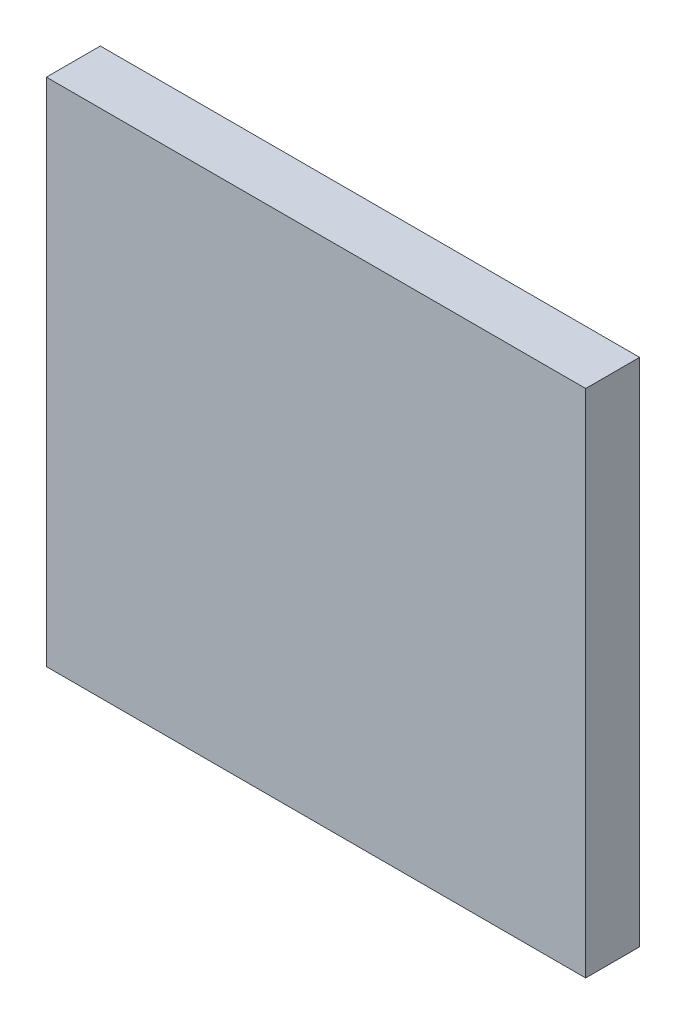
SolidWorks part; units mm, degrees
ref_plane "Front Plane" through (0, 0, 0) normal (0, 0, 1) x (1, 0, 0)
ref_plane "Top Plane" through (0, 0, 0) normal (0, 1, 0) x (1, 0, 0)
ref_plane "Right Plane" through (0, 0, 0) normal (1, 0, 0) x (0, 0, -1)
sketch "Sketch1" plane through (0, 0, 0) normal (0, 0, 1) x (1, 0, 0)
  circle A0 centre (0, 0) radius 19.939
  dimension "D1" = 39.878
extrude "circle extrude" add sketch "Sketch1" along normal blind 12.7
sketch "Sketch3" plane through (0, 0, 0) normal (1, 0, 0) x (0, 0, -1)
  line L0 (0, 19.8374) -> (0, -19.8374) construction
  line L1 (-12.7, 19.939) -> (0, 19.939)
  line L2 (-12.7, 19.939) -> (-12.7, -19.939)
  line L3 (-12.7, -19.939) -> (0, -19.939)
  line L4 (0, 19.939) -> (0, -19.939)
  line L5 (-12.7, -19.939) -> (0, -19.939) construction
extrude "rectangle extrude" add sketch "Sketch3" along normal blind 68.58
sketch "Sketch2" plane through (0, 0, 12.7) normal (0, 0, 1) x (1, 0, 0)
  circle A0 centre (0, 0) radius 18.034
  dimension "D1" = 36.068
extrude "cricle cut" cut sketch "Sketch2" against normal through all
sketch "Sketch4" plane through (0, 0, 12.7) normal (0, 0, 1) x (1, 0, 0)
  line L0 (68.58, 19.939) -> (68.58, -19.939) construction
  line L1 (0, 18.034) -> (66.675, 18.034)
  line L2 (0, 18.034) -> (0, -18.034)
  line L3 (0, -18.034) -> (66.675, -18.034)
  line L4 (66.675, 18.034) -> (66.675, -18.034)
  line L5 (68.58, -19.939) -> (0, -19.939) construction
  circle A0 centre (0, 0) radius 18.034 construction
  dimension "D1" = 1.905
  dimension "D2" = 1.905
extrude "frame cut" cut sketch "Sketch4" against normal through all flip side to cut
sketch "Sketch8" plane through (0, 0, 12.7) normal (0, 0, 1) x (1, 0, 0)
  line L6 (0, -18.034) -> (66.675, -18.034) construction
  line L7 (36.068, 18.034) -> (66.675, 18.034)
  line L8 (66.675, 18.034) -> (66.675, -18.034)
  line L9 (66.675, -18.034) -> (36.068, -18.034)
  line L10 (66.675, 18.034) -> (0, 18.034) construction
  arc A1 (36.068, -18.034) -> (36.068, 18.034) centre (36.068, 0) ccw
  dimension "D1" = 36.068
extrude "end cut" [suppressed] cut sketch "Sketch8" against normal through all
sketch "Sketch10" plane through (0, 0, 0) normal (0, 0, -1) x (-1, 0, 0)
  line L2 (0, 18.034) -> (-66.675, 18.034)
  line L3 (-66.675, -18.034) -> (0, -18.034)
  line L4 (0, 18.034) -> (-66.675, 18.034)
  line L5 (-66.675, -18.034) -> (0, -18.034)
  line L7 (-66.675, 18.034) -> (-66.675, -18.034)
  line L8 (-66.675, 18.034) -> (-66.675, -18.034)
  arc A3 (0, 18.034) -> (0, -18.034) centre (0, 0) ccw
  arc A5 (0, 18.034) -> (0, -18.034) centre (0, 0) ccw
  dimension "D1" = 0
extrude "extension" [suppressed] add sketch "Sketch10" along normal blind 2.54
ref_plane "Plane2" [suppressed] through (20.32, 0, 0) normal (1, 0, 0) x (0, 0, -1)
sketch "Sketch11" [suppressed] plane through (20.32, 0, 0) normal (1, 0, 0) x (0, 0, -1)
  line L0 (2.54, 18.034) -> (-7.62, 18.034) construction
  line L1 (0, -18.034) -> (-5.08, -18.034)
  line L2 (0, -18.034) -> (0, 18.034)
  line L3 (0, 18.034) -> (-5.08, 18.034)
  line L4 (-5.08, -18.034) -> (-5.08, 18.034)
  line L5 (0, -18.034) -> (-5.08, 18.034) construction
  line L6 (0, 18.034) -> (-5.08, -18.034) construction
  line L7 (2.54, -18.034) -> (-7.62, -18.034) construction
  point P0 (-2.54, 0)
  dimension "D1" = 2.54
  dimension "D2" = 5.08
extrude "middle" [suppressed] cut sketch "Sketch11" along normal through all
sketch "Sketch12" [suppressed] plane through (0, 0, 0) normal (0, 0, 1) x (1, 0, 0)
  line L0 (20.32, -5.588) -> (20.32, 5.588) construction
  line L1 (0, 18.034) -> (61.595, 18.034) construction
  line L2 (2.286, 18.034) -> (0, 18.034)
  line L3 (0, 18.034) -> (0, -18.034)
  line L4 (0, -18.034) -> (2.286, -18.034)
  arc A0 (2.286, -18.034) -> (2.286, 18.034) centre (2.286, 0) ccw
  dimension "D1" = 36.068
extrude "circle extension" [suppressed] cut sketch "Sketch12" along normal blind 5.08 flip side to cut
sketch "Sketch13" plane through (66.675, 0, 0) normal (1, 0, 0) x (0, 0, -1)
  line L1 (-3.81, -18.034) -> (-8.89, -18.034)
  line L2 (-3.81, -18.034) -> (-3.81, 18.034)
  line L3 (-3.81, 18.034) -> (-8.89, 18.034)
  line L4 (-8.89, -18.034) -> (-8.89, 18.034)
  line L5 (-3.81, -18.034) -> (-8.89, 18.034) construction
  line L6 (-3.81, 18.034) -> (-8.89, -18.034) construction
  line L7 (0, -18.034) -> (-12.7, -18.034) construction
  line L8 (0, 18.034) -> (-12.7, 18.034) construction
  point P0 (-6.35, 0)
  dimension "D1" = 6.35
  dimension "D2" = 5.08
extrude "back cut" cut sketch "Sketch13" against normal blind 38.1
sketch "Sketch14" plane through (28.575, 0, 0) normal (1, 0, 0) x (0, 0, -1)
  circle A0 centre (-6.35, 0) radius 1.905
  dimension "D2" = 3.81
  dimension "D1" = 6.35
extrude "for spring extrude" add sketch "Sketch14" along normal blind 2.54
sketch "Sketch15" plane through (0, 18.034, 0) normal (0, 1, 0) x (1, 0, 0)
  line L0 (66.675, 0) -> (0, 0) construction
  line L1 (28.575, 0) -> (0, 0)
  line L3 (28.575, -12.7) -> (0, -12.7)
  line L4 (0, 0) -> (0, -12.7)
  line L6 (0, 0) -> (0, -12.7) construction
  line L7 (28.575, -4.445) -> (68.6889, -4.445)
  line L8 (68.6889, -4.445) -> (68.6889, -12.7)
  line L9 (68.6889, -12.7) -> (28.575, -12.7)
  line L10 (28.575, -4.445) -> (28.575, 0)
extrude "Cut-Extrude1" cut sketch "Sketch15" against normal through all
equation "\"wall_thickness\"= 0.125in"
equation "\"base_thickness\"= 0.25in"
